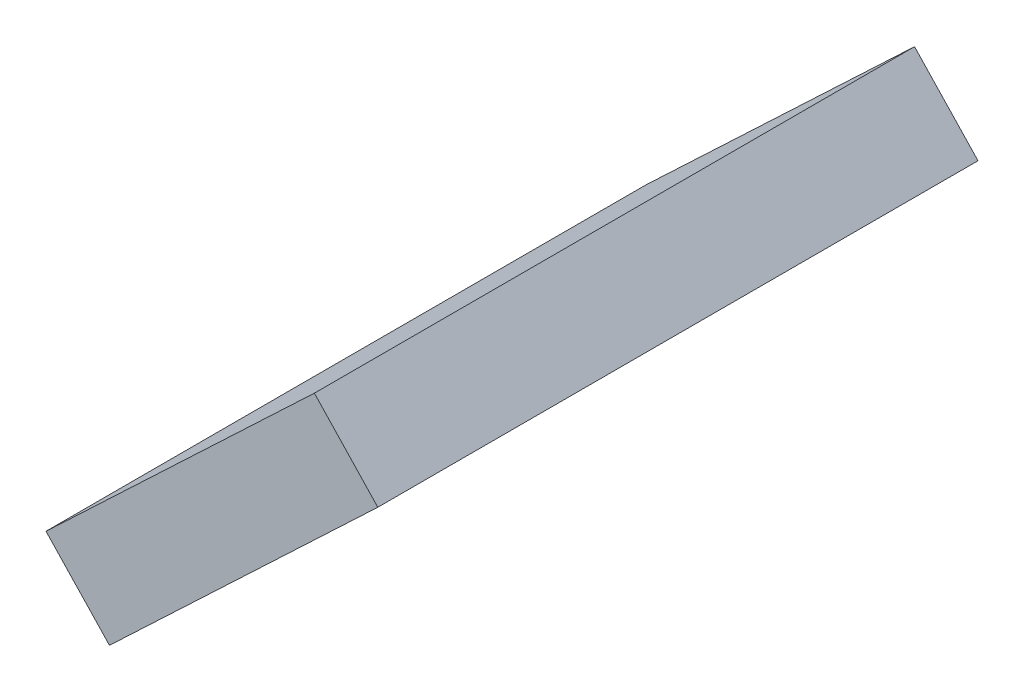
SolidWorks part; units mm, degrees
ref_plane "Front Plane" through (0, 0, 0) normal (0, 0, 1) x (1, 0, 0)
ref_plane "Top Plane" through (0, 0, 0) normal (0, 1, 0) x (1, 0, 0)
ref_plane "Right Plane" through (0, 0, 0) normal (1, 0, 0) x (0, 0, -1)
sketch "Sketch1" plane through (0, 0, 0) normal (0, 0, 1) x (1, 0, 0)
  line L0 (-379.2517, -354.2564) -> (-321.1226, -299.2927)
  line L1 (-379.2517, -354.2564) -> (-365.5108, -368.7887)
  line L2 (-321.1226, -299.2927) -> (-307.3817, -313.825)
  line L3 (-365.5108, -368.7887) -> (-307.3817, -313.825)
  point P0 (-379.2517, -354.2564)
  dimension "D1" = 20
  dimension "D2" = 80
extrude "Boss-Extrude2" add sketch "Sketch1" along normal blind 130
